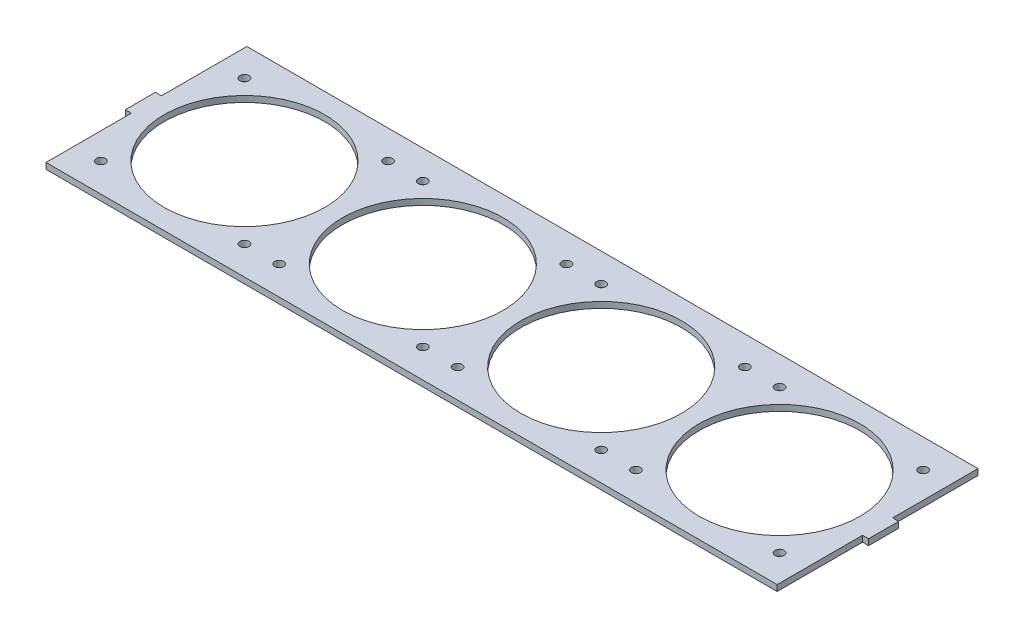
SolidWorks part; units mm, degrees
ref_plane "Front Plane" through (0, 0, 0) normal (0, 0, 1) x (1, 0, 0)
ref_plane "Top Plane" through (0, 0, 0) normal (0, 1, 0) x (1, 0, 0)
ref_plane "Right Plane" through (0, 0, 0) normal (1, 0, 0) x (0, 0, -1)
sketch "Sketch1" plane through (0, 0, 0) normal (0, 1, 0) x (1, 0, 0)
  line L1 (75.4621, 64.9352) -> (-288.5379, 64.9352)
  line L2 (75.4621, 64.9352) -> (75.4621, 22.4352)
  line L3 (75.4621, -35.0648) -> (-288.5379, -35.0648)
  line L4 (-288.5379, 64.9352) -> (-288.5379, 22.4352)
  line L5 (78.4621, 7.4352) -> (78.4621, 22.4352)
  line L8 (78.4621, 22.4352) -> (75.4621, 22.4352)
  line L10 (78.4621, 7.4352) -> (75.4621, 7.4352)
  line L12 (75.4621, 7.4352) -> (75.4621, -35.0648)
  line L14 (-291.5379, 7.4352) -> (-288.5379, 7.4352)
  line L15 (-291.5379, 22.4352) -> (-288.5379, 22.4352)
  line L16 (-291.5379, 7.4352) -> (-291.5379, 22.4352)
  line L17 (-288.5379, 7.4352) -> (-288.5379, -35.0648)
  circle A0 centre (-239.7379, 14.9352) radius 40
  circle A4 centre (-203.9879, 50.6852) radius 2.25
  circle A5 centre (-203.9879, -20.8148) radius 2.25
  circle A6 centre (-275.4879, -20.8148) radius 2.25
  circle A7 centre (-275.4879, 50.6852) radius 2.25
  circle A8 centre (-186.6879, 50.6852) radius 2.25
  circle A9 centre (-150.9379, 14.9352) radius 40
  circle A10 centre (-115.1879, 50.6852) radius 2.25
  circle A11 centre (-186.6879, -20.8148) radius 2.25
  circle A12 centre (-115.1879, -20.8148) radius 2.25
  circle A13 centre (-97.8879, 50.6852) radius 2.25
  circle A14 centre (-62.1379, 14.9352) radius 40
  circle A15 centre (-26.3879, 50.6852) radius 2.25
  circle A16 centre (-97.8879, -20.8148) radius 2.25
  circle A17 centre (-26.3879, -20.8148) radius 2.25
  circle A18 centre (-9.0879, 50.6852) radius 2.25
  circle A19 centre (26.6621, 14.9352) radius 40
  circle A20 centre (62.4121, 50.6852) radius 2.25
  circle A21 centre (-9.0879, -20.8148) radius 2.25
  circle A22 centre (62.4121, -20.8148) radius 2.25
  dimension "D3" = 80
  dimension "D6" = 15
  dimension "D7" = 3
  dimension "D8" = 4.5
  dimension "D1" = 364
  dimension "D2" = 100
  dimension "D4" = 48.8
  dimension "D5" = 4
extrude "Boss-Extrude1" add sketch "Sketch1" along normal blind 3
